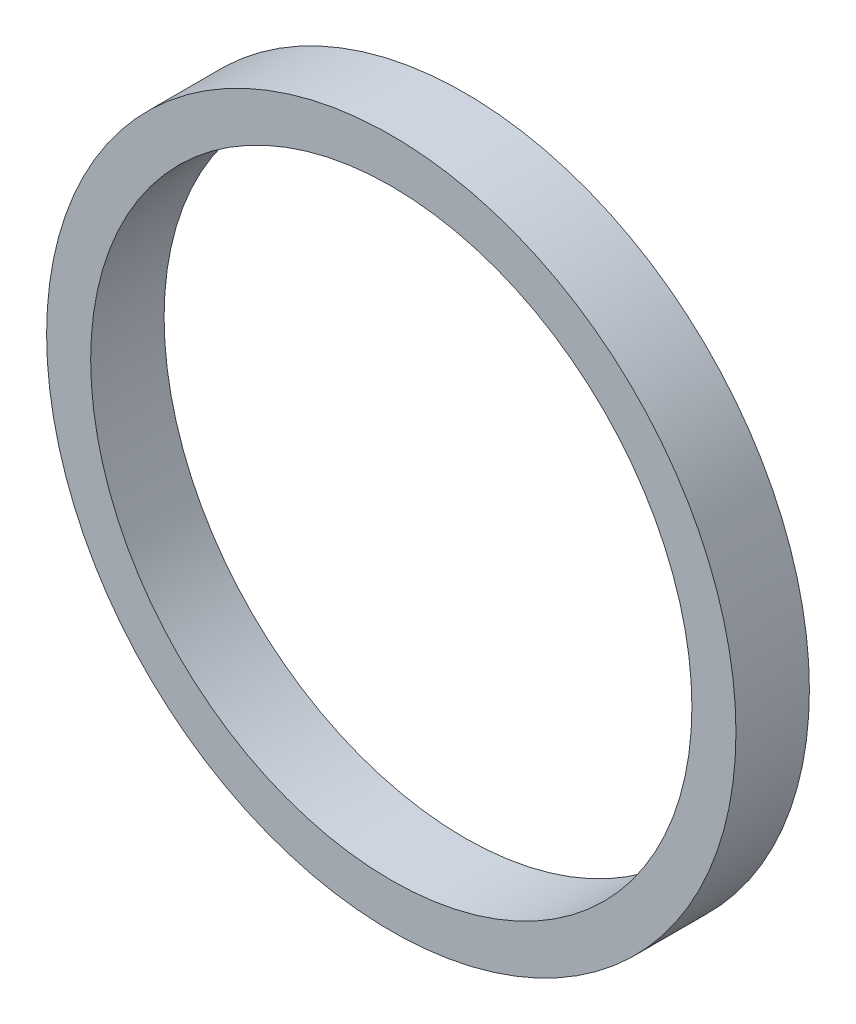
SolidWorks part; units mm, degrees
ref_plane "Front Plane" through (0, 0, 0) normal (0, 0, 1) x (1, 0, 0)
ref_plane "Top Plane" through (0, 0, 0) normal (0, 1, 0) x (1, 0, 0)
ref_plane "Right Plane" through (0, 0, 0) normal (1, 0, 0) x (0, 0, -1)
sketch "Sketch1" plane through (0, 0, 0) normal (0, 0, 1) x (1, 0, 0)
  circle A0 centre (0, 0) radius 37.55
  circle A1 centre (0, 0) radius 32.75
  dimension "D1" = 75.1
  dimension "D2" = 65.5
extrude "Boss-Extrude1" add sketch "Sketch1" along normal blind 8 contours A1 | A0
